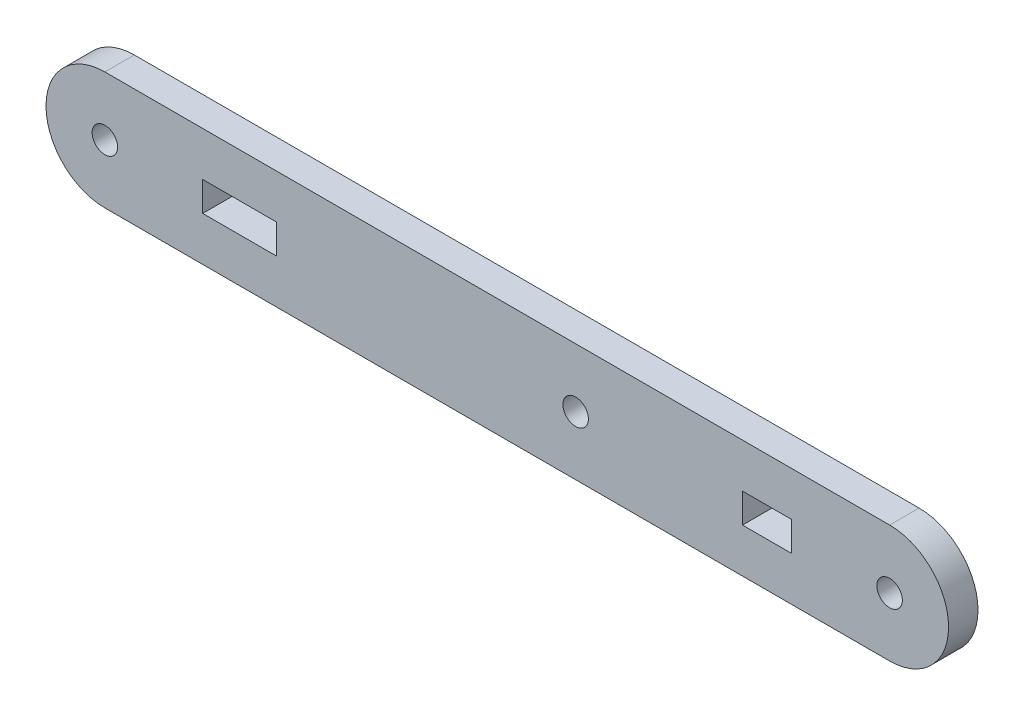
SolidWorks part; units mm, degrees
ref_plane "前视基准面" through (0, 0, 0) normal (0, 0, 1) x (1, 0, 0)
ref_plane "上视基准面" through (0, 0, 0) normal (0, 1, 0) x (1, 0, 0)
ref_plane "右视基准面" through (0, 0, 0) normal (1, 0, 0) x (0, 0, -1)
ref_plane "基准面1" through (0, 0, 3) normal (0, 0, 1) x (1, 0, 0)
sketch "草图1" plane through (0, 0, 3) normal (0, 0, 1) x (1, 0, 0)
  line L0 (-49.3435, 0) -> (30.6182, 0)
  line L1 (30.6182, 12) -> (-49.3435, 12)
  line L2 (-31.8791, 4.4994) -> (-39.3783, 4.4994)
  line L3 (-39.3783, 4.4994) -> (-39.3783, 7.4995)
  line L4 (-39.3783, 7.4995) -> (-31.8791, 7.4995)
  line L5 (-31.8791, 7.4995) -> (-31.8791, 4.4994)
  line L6 (20.6213, 4.4994) -> (15.6218, 4.4994)
  line L7 (15.6218, 4.4994) -> (15.6218, 7.4995)
  line L8 (15.6218, 7.4995) -> (20.6213, 7.4995)
  line L9 (20.6213, 7.4995) -> (20.6213, 4.4994)
  circle A0 centre (30.6116, 6.0001) radius 1.3
  circle A1 centre (-1.3793, 6.0002) radius 1.3
  circle A2 centre (-49.3435, 6) radius 1.3
  arc A3 (30.6182, 0) -> (30.6182, 12) centre (30.6182, 6) ccw
  arc A4 (-49.3435, 12) -> (-49.3435, 0) centre (-49.3435, 6) ccw
extrude "凸台-拉伸1" add sketch "草图1" against normal blind 3
